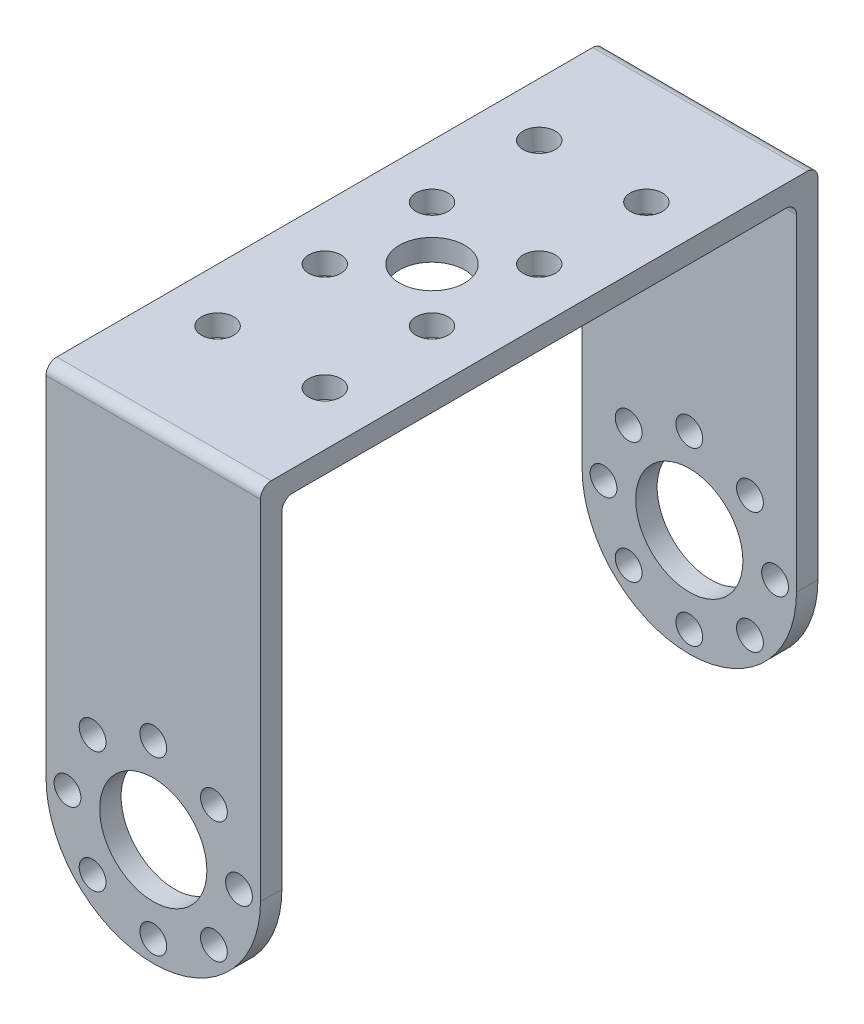
SolidWorks part; units mm, degrees
ref_plane "前视基准面" through (0, 0, 0) normal (0, 0, 1) x (1, 0, 0)
ref_plane "上视基准面" through (0, 0, 0) normal (0, 1, 0) x (1, 0, 0)
ref_plane "右视基准面" through (0, 0, 0) normal (1, 0, 0) x (0, 0, -1)
sketch "草图1" plane through (0, 0, 0) normal (1, 0, 0) x (0, 0, -1)
  line L0 (-24, -25) -> (-24, 23)
  line L1 (-26, -25) -> (-24, -25)
  line L2 (-26, -25) -> (-26, 25)
  line L3 (-26, 25) -> (26, 25)
  line L4 (26, -25) -> (26, 25)
  line L5 (-26, -25) -> (26, 25) construction
  line L6 (-26, 25) -> (26, -25) construction
  line L7 (-24, 23) -> (24, 23)
  line L8 (24, 23) -> (24, -25)
  line L9 (24, -25) -> (26, -25)
  point P0 (0, 0)
  dimension "D1" = 52
  dimension "D2" = 50
  dimension "D3" = 2
  dimension "D4" = 2
  dimension "D5" = 2
extrude "凸台-拉伸1" add sketch "草图1" along normal blind 20
fillet "圆角1" radius 1 4 edges at (10, 23, -24) (10, 23, 24) (10, 25, -26) (10, 25, 26)
sketch "草图2" plane through (0, 0, 26) normal (0, 0, 1) x (1, 0, 0)
  line L2 (0, -8.5) -> (0, -25)
  line L3 (0, -25) -> (20, -18.5)
  line L4 (20, -18.5) -> (20, -8.5)
  arc A0 (0, -8.5) -> (20, -8.5) centre (10, -8.5) ccw
  line M2 (20, -25) -> (20, 24)
  line M4 (0, 24) -> (0, -25)
  line M5 (0, -25) -> (20, -25)
extrude "切除-拉伸1" cut sketch "草图2" against normal blind 50000 contours A0 M4 M5 | A0 L3 M2
sketch "草图3" plane through (0, 0, 26) normal (0, 0, 1) x (1, 0, 0)
  circle A0 centre (10, -8.5) radius 5
  dimension "D1" = 10
extrude "切除-拉伸2" cut sketch "草图3" against normal blind 500
sketch "草图4" plane through (0, 0, 26) normal (0, 0, 1) x (1, 0, 0)
  line L0 (-2.3741, -8.5) -> (25.5776, -8.5) construction
  circle A0 centre (18, -8.5) radius 1.25
  circle A1 centre (10, -8.5) radius 5 construction
  dimension "D1" = 2.5
  dimension "D2" = 8
extrude "切除-拉伸3" cut sketch "草图4" against normal blind 5000
pattern_circular "阵列(圆周)1" count 8 over 360 about axis through (10, -8.5, 0) along (0, 0, 1) of "切除-拉伸3"
sketch "草图5" plane through (0, 25, 0) normal (0, 1, 0) x (1, 0, 0)
  line L0 (-9.8163, 0) -> (34.6252, 0) construction
  line L1 (10, 33.3615) -> (10, -35.0916) construction
  line L2 (-3.2827, 5) -> (39.003, 5) construction
  line L3 (-3.9792, 15) -> (33.3318, 15) construction
  circle A0 centre (10, 0) radius 3.05
  circle A1 centre (15, 15) radius 1.5
  circle A2 centre (5, 15) radius 1.5
  circle A3 centre (5, 5) radius 1.5
  circle A4 centre (15, 5) radius 1.5
  circle A5 centre (15, -5) radius 1.5
  circle A6 centre (5, -5) radius 1.5
  circle A7 centre (5, -15) radius 1.5
  circle A8 centre (15, -15) radius 1.5
  dimension "D1" = 6.1
  dimension "D4" = 3
  dimension "D5" = 5
  dimension "D2" = 5
  dimension "D3" = 10
  dimension "D6" = 5
  dimension "D7" = 5
  dimension "D8" = 5
extrude "切除-拉伸4" cut sketch "草图5" against normal blind 5000
